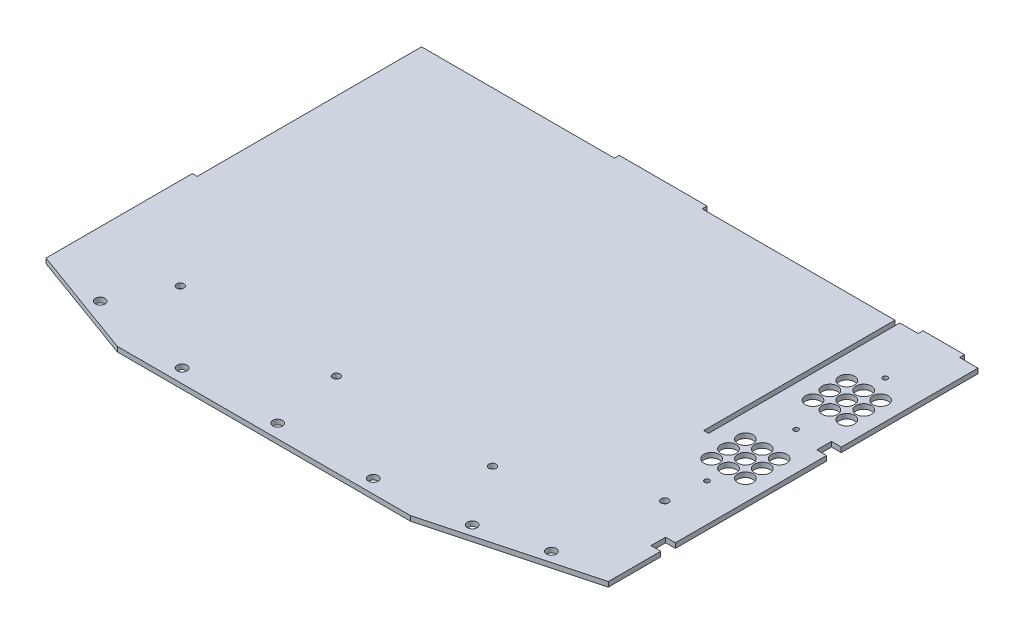
SolidWorks part; units mm, degrees
material "6061-T6 (SS)"
ref_plane "X-Y Datum" through (0, 0, 0) normal (0, 0, 1) x (1, 0, 0)
ref_plane "X-Z Datum" through (0, 0, 0) normal (0, 1, 0) x (1, 0, 0)
ref_plane "Y-Z Datum" through (0, 0, 0) normal (1, 0, 0) x (0, 0, -1)
sketch "Sketch1" plane through (0, 0, 0) normal (0, 0, 1) x (1, 0, 0)
  line L1 (-154.0408, -1.5875) -> (154.0408, -1.5875)
  line L2 (-154.0408, -1.5875) -> (-154.0408, 1.5875)
  line L3 (-154.0408, 1.5875) -> (154.0408, 1.5875)
  line L4 (154.0408, -1.5875) -> (154.0408, 1.5875)
  line L5 (-154.0408, -1.5875) -> (154.0408, 1.5875) construction
  line L6 (-154.0408, 1.5875) -> (154.0408, -1.5875) construction
  point P0 (0, 0)
  dimension "D1" = 3.175
  dimension "D2" = 308.0817
extrude "Boss-Extrude1" add sketch "Sketch1" along normal blind 267.83
sketch "Sketch3" plane through (154.0408, 0, 0) normal (1, 0, 0) x (0, 0, -1)
  line L9 (0, -1.5875) -> (0, 1.5875)
  line L10 (0, 1.5875) -> (-267.83, 1.5875)
  line L11 (-267.83, 1.5875) -> (-267.83, -1.5875)
  line L12 (-267.83, -1.5875) -> (0, -1.5875)
  line L13 (0, -1.5875) -> (0, 1.5875)
  line L14 (0, 1.5875) -> (-267.83, 1.5875)
  line L15 (-267.83, 1.5875) -> (-267.83, -1.5875)
  line L16 (-267.83, -1.5875) -> (0, -1.5875)
  dimension "D1" = 0
extrude "Boss-Extrude3" add sketch "Sketch3" along normal blind 3.175
sketch "Sketch4" plane through (0, 0, 267.83) normal (0, 0, 1) x (1, 0, 0)
  line L1 (157.2158, -1.5875) -> (208.1047, -1.5875)
  line L2 (157.2158, -1.5875) -> (157.2158, 1.5875)
  line L3 (157.2158, 1.5875) -> (208.1047, 1.5875)
  line L4 (208.1047, -1.5875) -> (208.1047, 1.5875)
  dimension "D1" = 3.175
  dimension "D2" = 50.8889
extrude "Boss-Extrude4" add sketch "Sketch4" against normal blind 267.83
sketch "Sketch6" plane through (0, 1.5875, 0) normal (0, 1, 0) x (1, 0, 0)
  line L0 (106.5047, -267.83) -> (106.5047, -223.38)
  line L1 (208.1047, -267.83) -> (-154.0408, -267.83) construction
  line L2 (208.1047, -223.38) -> (106.5047, -223.38)
  line L3 (208.1047, 0) -> (208.1047, -267.83) construction
  line L5 (106.5047, -267.83) -> (208.1047, -240.6064)
  line L7 (-154.0408, -267.83) -> (208.1047, -267.83) construction
  line L8 (208.1047, 0) -> (208.1047, -267.83) construction
  line L9 (208.1047, 0) -> (208.1047, -267.83)
  line M9 (-154.0408, -267.83) -> (208.1047, -267.83)
  line M10 (208.1047, -267.83) -> (208.1047, 0)
  dimension "D1" = 44.45
  dimension "D2" = 101.6
  dimension "D3" = 15
extrude "Cut-Extrude1" cut sketch "Sketch6" against normal through all contours L5 M9 M10
sketch "Sketch17" plane through (-154.0408, 0, 0) normal (-1, 0, 0) x (0, 0, 1)
  line L15 (267.83, -1.5875) -> (267.83, 1.5875)
  line L16 (0, -1.5875) -> (267.83, -1.5875)
  line L17 (267.83, -1.5875) -> (267.83, 1.5875)
  line L18 (267.83, 1.5875) -> (0, 1.5875)
  line L19 (0, 1.5875) -> (0, -1.5875)
  line L20 (0, -1.5875) -> (267.83, -1.5875)
  line L22 (267.83, 1.5875) -> (0, 1.5875)
  line L23 (0, 1.5875) -> (0, -1.5875)
  dimension "D1" = 0
extrude "Boss-Extrude5" add sketch "Sketch17" along normal blind 3.175
sketch "Sketch11" plane through (0, -1.5875, 0) normal (0, -1, 0) x (1, 0, 0)
  line L0 (-84.2547, 267.83) -> (-84.2547, 241.2743)
  line L1 (-157.2158, 267.83) -> (106.5047, 267.83) construction
  line L2 (-157.2158, 241.2743) -> (-84.2547, 241.2743)
  line L4 (-157.2158, 241.2743) -> (-84.2547, 267.83)
  line L6 (-157.2158, 267.83) -> (106.5047, 267.83) construction
  line L7 (-157.2158, 0) -> (-157.2158, 267.83) construction
  dimension "D2" = 26.5557
  dimension "D3" = 20
extrude "Cut-Extrude3" cut sketch "Sketch11" against normal through all
sketch "Sketch25" plane through (0, -1.5875, 0) normal (0, -1, 0) x (1, 0, 0)
  line L0 (-157.2285, 241.2697) -> (-83.9953, 267.9244) construction
  line L1 (-50.9753, 267.83) -> (-50.9753, 258.94)
  line L2 (-157.2158, 241.2743) -> (-84.2547, 267.83) construction
  line L3 (-118.0865, 255.5162) -> (-115.3222, 247.9214)
  line L5 (-84.2547, 267.83) -> (106.5047, 267.83) construction
  line L6 (-50.9753, 258.94) -> (11.2547, 258.94) construction
  line L7 (11.2547, 258.94) -> (73.4847, 258.94) construction
  line L8 (172.3981, 250.1739) -> (172.5447, 242.093)
  line L9 (106.5047, 267.83) -> (208.1047, 240.6064) construction
  line L10 (172.5447, 242.093) -> (131.9047, 252.9824) construction
  circle A0 centre (-115.3222, 247.9214) radius 3.175
  circle A1 centre (-50.9753, 258.94) radius 3.175
  circle A2 centre (11.2547, 258.94) radius 3.175
  circle A3 centre (73.4847, 258.94) radius 3.175
  circle A4 centre (172.5447, 242.093) radius 3.175
  circle A5 centre (131.9047, 252.9824) radius 3.175
  dimension "D2" = 90
  dimension "D3" = 6.35
  dimension "D13" = 8.89
  dimension "D4" = 7.7676
  dimension "D1" = 8.0823
  dimension "D5" = 33.02
  dimension "D6" = 62.23
  dimension "D7" = 62.23
  dimension "D8" = 33.02
  dimension "D9" = 35.56
  dimension "D10" = 73.96
  dimension "D11" = 40.64
  dimension "D12" = 8.0823
extrude "Cut-Extrude8" cut sketch "Sketch25" against normal blind 3.175
sketch "Sketch27" plane through (0, -1.5875, 0) normal (0, -1, 0) x (1, 0, 0)
  circle A1 centre (172.4867, 137.7748) radius 5
  circle A3 centre (183.4867, 137.7748) radius 5
  circle A11 centre (194.4867, 137.7748) radius 5
  circle A12 centre (194.4867, 126.7748) radius 5
  circle A13 centre (194.4867, 115.7748) radius 5
  circle A14 centre (183.4867, 126.7748) radius 5
  circle A15 centre (183.4867, 115.7748) radius 5
  circle A16 centre (172.4867, 115.7748) radius 5
  circle A17 centre (172.4867, 126.7748) radius 5
  circle A27 centre (194.4867, 71.7748) radius 5
  circle A28 centre (194.4867, 60.7748) radius 5
  circle A29 centre (194.4867, 49.7748) radius 5
  circle A30 centre (183.4867, 71.7748) radius 5
  circle A31 centre (183.4867, 60.7748) radius 5
  circle A32 centre (183.4867, 49.7748) radius 5
  circle A33 centre (172.4867, 49.7748) radius 5
  circle A34 centre (172.4867, 60.7748) radius 5
  circle A35 centre (172.4867, 71.7748) radius 5
extrude "Cut-Extrude9" cut sketch "Sketch27" against normal through all
sketch "Sketch31" plane through (0, -1.5875, 0) normal (0, -1, 0) x (1, 0, 0)
  circle A1 centre (183.4867, 151.7748) radius 2.4 construction
  circle A2 centre (183.4867, 151.7748) radius 1.5875
  dimension "D1" = 3.175
extrude "Cut-Extrude10" cut sketch "Sketch31" against normal through all both and the other way through all
pattern_linear "LPattern1" count 3 spacing 58 along (0, 0, -1) of "Cut-Extrude10"
sketch "Sketch34" plane through (0, -1.5875, 0) normal (0, -1, 0) x (1, 0, 0)
  point P0 (180.965, 176.776)
  point P1 (-97.7709, 213.285)
  point P2 (3.829, 213.285)
  point P3 (105.4291, 213.285)
hole_wizard "M4 Clearance Hole1" positions "Sketch34" profile "Sketch35" hole size "M4" standard "ANSI Metric" end condition through all
sketch "Sketch35" plane through (180.965, -1.5875, 176.776) normal (1, 0, 0) x (0, 0, -1)
  line L0 (0, 0) -> (0, 3.175)
  line L1 (0, 3.175) -> (2.4, 3.175)
  line L2 (2.4, 3.175) -> (2.4, 0)
  line L5 (2.4, 0) -> (0, 0)
  line L11 (0, -6.35) -> (0, 107.95) construction
  dimension "Thru Hole Dia." = 4.8
  dimension "Thru Hole Depth" = 3.175
sketch "Sketch36" plane through (0, 0, 0) normal (0, 0, -1) x (-1, 0, 0)
  line L0 (28.6512, 1.6677) -> (-28.6512, 1.6677) construction
  line L1 (0, 1.5875) -> (0, -1.5875) construction
  line L2 (-208.1047, 1.5875) -> (157.2158, 1.5875) construction
  line L3 (157.2158, -1.5875) -> (-208.1047, -1.5875) construction
  line L5 (28.575, -1.5875) -> (-28.575, -1.5875)
  line L6 (28.575, -1.5875) -> (28.575, 1.5875)
  line L7 (28.575, 1.5875) -> (-28.575, 1.5875)
  line L8 (-28.575, -1.5875) -> (-28.575, 1.5875)
  line L9 (28.575, -1.5875) -> (-28.575, 1.5875) construction
  line L10 (28.575, 1.5875) -> (-28.575, -1.5875) construction
  line L11 (-169.0911, 1.6637) -> (-196.231, 1.6637) construction
  line L12 (-182.661, 1.5875) -> (-182.661, -1.5875) construction
  line L13 (-157.216, 1.5875) -> (-195.316, 1.5875) construction
  line L14 (-169.1673, -1.5875) -> (-196.1548, -1.5875)
  line L15 (-169.1673, -1.5875) -> (-169.1673, 1.5875)
  line L16 (-169.1673, 1.5875) -> (-196.1548, 1.5875)
  line L17 (-196.1548, -1.5875) -> (-196.1548, 1.5875)
  line L18 (-169.1673, -1.5875) -> (-196.1548, 1.5875) construction
  line L19 (-169.1673, 1.5875) -> (-196.1548, -1.5875) construction
  point P0 (0, 1.6677)
  point P1 (0, 1.6677)
  point P11 (0, 0)
  point P16 (-182.661, 1.6637)
  point P21 (-182.661, 0)
  dimension "D1" = 57.15
  dimension "D2" = 26.9875
extrude "Boss-Extrude6" add sketch "Sketch36" along normal blind 3.175
sketch "Sketch37" plane through (0, -1.5875, 0) normal (0, -1, 0) x (1, 0, 0)
  line L0 (157.216, 124.442) -> (157.216, 50.8) construction
  line L1 (154.041, 124.442) -> (157.216, 124.442) construction
  line L2 (154.041, 124.442) -> (154.041, 50.8) construction
  line L3 (157.216, 124.442) -> (157.216, 0)
  line L4 (154.041, 124.442) -> (157.216, 124.442)
  line L5 (154.041, 124.442) -> (154.041, 0)
  line L6 (28.575, 0) -> (169.1673, 0) construction
  line L7 (154.041, 0) -> (157.216, 0)
  line L8 (153.9648, 124.5182) -> (157.2922, 124.5182)
  line L9 (157.2922, 124.5182) -> (157.2922, -0.0762)
  line L10 (153.9648, -0.0762) -> (157.2922, -0.0762)
  line L11 (153.9648, 124.5182) -> (153.9648, -0.0762)
  line M38 (28.575, 0) -> (169.1673, 0)
  dimension "D1" = 0.0762
extrude "Cut-Extrude11" cut sketch "Sketch37" against normal through all contours L4 L5 L3 M38
sketch "Sketch38" plane through (0, -1.5875, 0) normal (0, -1, 0) x (1, 0, 0)
  line L0 (-157.292, 146.1005) -> (-153.9646, 146.1005)
  line L1 (-157.2158, 0) -> (-154.0408, 0)
  line L2 (-157.2158, 0) -> (-157.2158, 146.0243)
  line L3 (-157.2158, 146.0243) -> (-154.0408, 146.0243)
  line L4 (-154.0408, 0) -> (-154.0408, 146.0243)
  line L5 (-153.9646, -0.0762) -> (-153.9646, 146.1005)
  line L6 (-157.292, -0.0762) -> (-153.9646, -0.0762)
  line L7 (-157.292, -0.0762) -> (-157.292, 146.1005)
  line M43 (-157.2158, 241.2743) -> (-157.2158, 0)
  line M44 (-157.2158, 0) -> (-28.575, 0)
  dimension "D1" = 3.175
  dimension "D2" = 95.25
  dimension "D3" = 0.0762
extrude "Cut-Extrude12" cut sketch "Sketch38" against normal through all contours L4 L3 M44 M43
sketch "Sketch39" plane through (0, -1.5875, 0) normal (0, -1, 0) x (1, 0, 0)
  line L0 (208.1809, 98.6135) -> (201.6785, 98.6135)
  line L1 (201.6785, 98.6135) -> (201.6785, 88.9361)
  line L2 (201.6785, 88.9361) -> (208.1809, 88.9361)
  line L3 (208.1809, 88.9361) -> (208.1809, 98.6135)
  line L4 (208.1047, 196.9623) -> (208.1047, 206.4873)
  line L5 (208.1047, 206.4873) -> (201.7547, 206.4873)
  line L6 (201.7547, 206.4873) -> (201.7547, 196.9623)
  line L7 (201.7547, 196.9623) -> (208.1047, 196.9623)
  line L8 (208.1047, 196.9623) -> (208.1047, 206.4873)
  line L9 (208.1047, 206.4873) -> (201.7547, 206.4873)
  line L10 (201.7547, 206.4873) -> (201.7547, 196.9623)
  line L11 (201.7547, 196.9623) -> (208.1047, 196.9623)
  line L12 (208.1047, 89.0123) -> (208.1047, 98.5373)
  line L13 (208.1047, 98.5373) -> (201.7547, 98.5373)
  line L14 (201.7547, 98.5373) -> (201.7547, 89.0123)
  line L15 (201.7547, 89.0123) -> (208.1047, 89.0123)
  line L16 (208.1047, 89.0123) -> (208.1047, 98.5373)
  line L17 (208.1047, 98.5373) -> (201.7547, 98.5373)
  line L18 (201.7547, 98.5373) -> (201.7547, 89.0123)
  line L19 (201.7547, 89.0123) -> (208.1047, 89.0123)
  line L20 (208.1809, 206.5635) -> (201.6785, 206.5635)
  line L21 (201.6785, 206.5635) -> (201.6785, 196.8861)
  line L22 (201.6785, 196.8861) -> (208.1809, 196.8861)
  line L23 (208.1809, 196.8861) -> (208.1809, 206.5635)
  dimension "D1" = 0
  dimension "D2" = 0
  dimension "D3" = 0.0762
extrude "Cut-Extrude13" cut sketch "Sketch39" against normal through all contours L18 L19 L16 L17 | L10 L11 L8 L9
